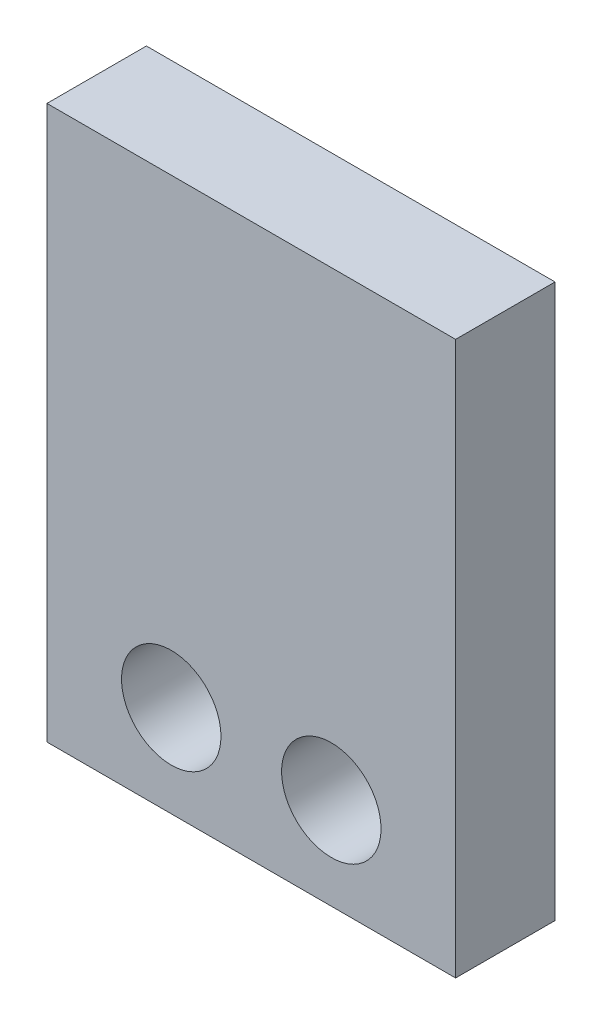
SolidWorks part; units mm, degrees
ref_plane "Front Plane" through (0, 0, 0) normal (0, 0, 1) x (1, 0, 0)
ref_plane "Top Plane" through (0, 0, 0) normal (0, 1, 0) x (1, 0, 0)
ref_plane "Right Plane" through (0, 0, 0) normal (1, 0, 0) x (0, 0, -1)
sketch "Sketch1" plane through (0, 0, 0) normal (0, 0, 1) x (1, 0, 0)
  line L5 (-255.0399, 48.8303) -> (-255.0399, -43.2856)
  line L6 (-140.2494, 48.8303) -> (-140.2494, -43.2856)
  line L8 (-585.2398, 92.7624) -> (-503.0441, 92.7624)
  line L9 (-503.0441, 92.7624) -> (-503.0441, -18.4852)
  line L10 (-503.0441, -18.4852) -> (-585.2398, -18.4852)
  line L11 (-585.2398, -18.4852) -> (-585.2398, 92.7624)
  circle A1 centre (-560.2398, 0) radius 10
  circle A2 centre (-528.0441, 0) radius 10
  point P12 (-562.5652, 0)
  dimension "D1" = 20
  dimension "D2" = 20
  dimension "D3" = 25
  dimension "D4" = 25
extrude "Boss-Extrude2" add sketch "Sketch1" along normal blind 20 contours L11 L10 L9 L8 A2 A1
